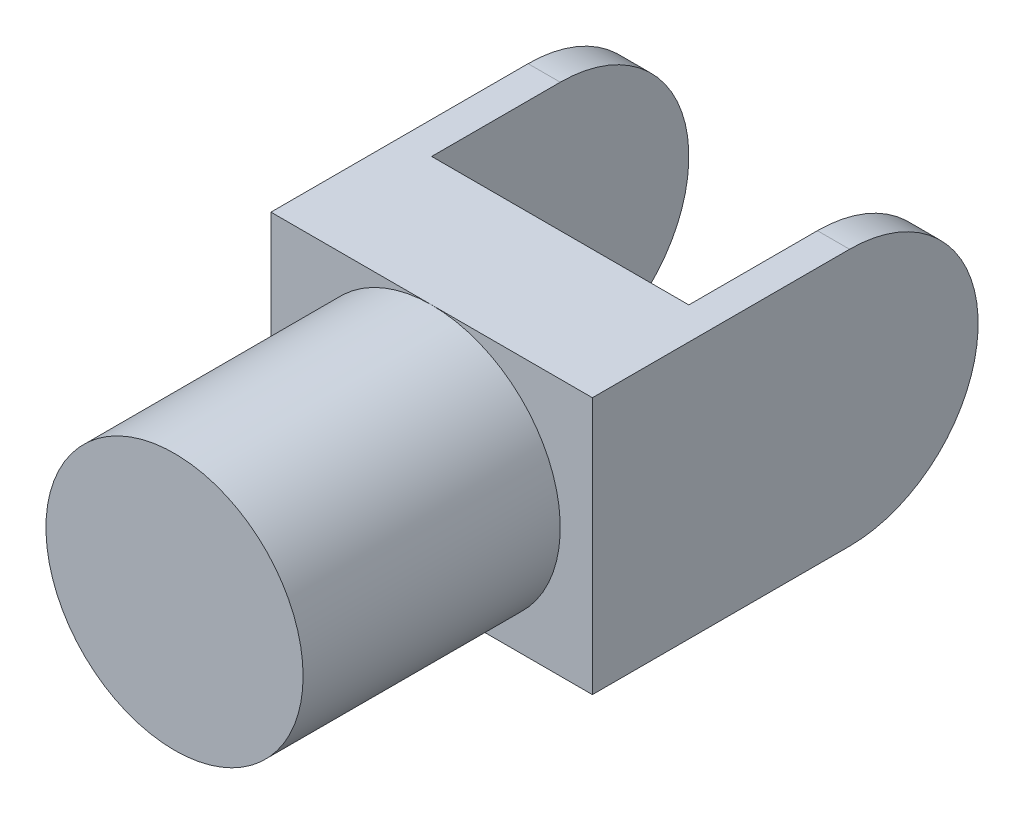
SolidWorks part; units mm, degrees
ref_plane "Front Plane" through (0, 0, 0) normal (0, 0, 1) x (1, 0, 0)
ref_plane "Top Plane" through (0, 0, 0) normal (0, 1, 0) x (1, 0, 0)
ref_plane "Right Plane" through (0, 0, 0) normal (1, 0, 0) x (0, 0, -1)
sketch "Sketch1" plane through (0, 0, 0) normal (1, 0, 0) x (0, 0, -1)
  line L0 (0, 40) -> (-80, 40)
  line L1 (-80, 40) -> (-80, -40)
  line L2 (-80, -40) -> (0, -40)
  arc A0 (0, -40) -> (0, 40) centre (0, 0) ccw
  dimension "D1" = 80
  dimension "D2" = 80
extrude "Boss-Extrude1" add sketch "Sketch1" along normal blind 100
sketch "Sketch2" plane through (0, 40, 0) normal (0, 1, 0) x (1, 0, 0)
  line L0 (100, 40) -> (0, 40) construction
  line L1 (10, 40) -> (90, 40)
  line L2 (10, 40) -> (10, -40)
  line L3 (10, -40) -> (90, -40)
  line L4 (90, 40) -> (90, -40)
  line L5 (0, 40) -> (0, 0) construction
  line L6 (100, 0) -> (100, 40) construction
  dimension "D1" = 10
  dimension "D2" = 10
  dimension "D3" = 80
extrude "Cut-Extrude1" cut sketch "Sketch2" against normal blind 100
sketch "Sketch3" plane through (0, 0, 80) normal (0, 0, 1) x (1, 0, 0)
  line L0 (0, 40) -> (0, -40) construction
  circle A0 centre (50, 0) radius 40
  dimension "D1" = 50
extrude "Boss-Extrude2" add sketch "Sketch3" along normal blind 80
